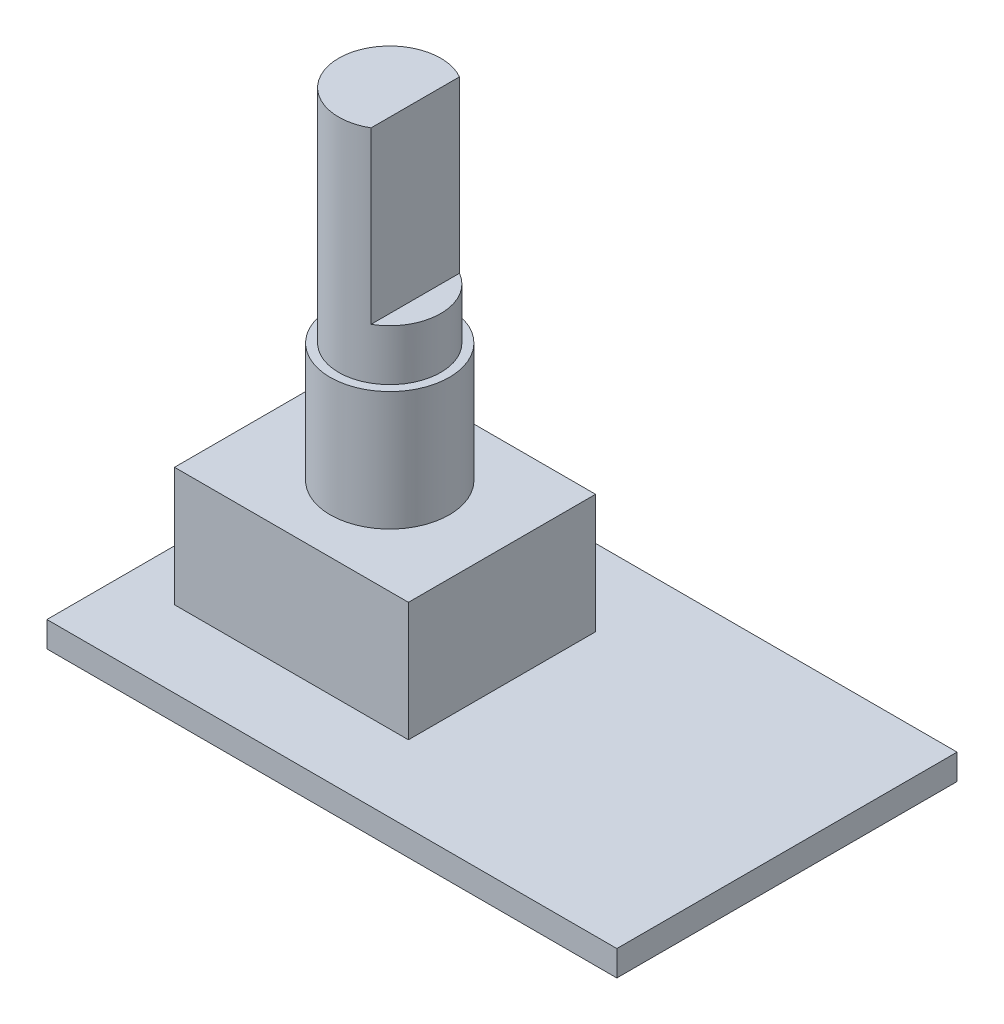
SolidWorks part; units mm, degrees
ref_plane "Front Plane" through (0, 0, 0) normal (0, 0, 1) x (1, 0, 0)
ref_plane "Top Plane" through (0, 0, 0) normal (0, 1, 0) x (1, 0, 0)
ref_plane "Right Plane" through (0, 0, 0) normal (1, 0, 0) x (0, 0, -1)
sketch "Sketch1" plane through (0, 0, 0) normal (0, 1, 0) x (1, 0, 0)
  line L1 (-8.8624, 8.0648) -> (24.6376, 8.0648)
  line L2 (-8.8624, 8.0648) -> (-8.8624, -11.9352)
  line L3 (-8.8624, -11.9352) -> (24.6376, -11.9352)
  line L4 (24.6376, 8.0648) -> (24.6376, -11.9352)
  dimension "D1" = 33.5
  dimension "D2" = 20
extrude "Boss-Extrude1" add sketch "Sketch1" along normal blind 1.5
sketch "Sketch2" plane through (0, 1.5, 0) normal (0, 1, 0) x (1, 0, 0)
  line L0 (24.6376, 8.0648) -> (-8.8624, 8.0648) construction
  line L1 (-5.8624, 3.5648) -> (7.8876, 3.5648)
  line L2 (-5.8624, 3.5648) -> (-5.8624, -7.4352)
  line L3 (-5.8624, -7.4352) -> (7.8876, -7.4352)
  line L4 (7.8876, 3.5648) -> (7.8876, -7.4352)
  line L5 (-8.8624, -11.9352) -> (24.6376, -11.9352) construction
  line L6 (-8.8624, 8.0648) -> (-8.8624, -11.9352) construction
  dimension "D1" = 4.5
  dimension "D2" = 4.5
  dimension "D3" = 3
  dimension "D4" = 13.75
extrude "Boss-Extrude2" add sketch "Sketch2" along normal blind 7
sketch "Sketch3" plane through (0, 8.5, 0) normal (0, 1, 0) x (1, 0, 0)
  line L0 (-5.8624, 3.5648) -> (-5.8624, -7.4352) construction
  circle A0 centre (1.1376, -1.7841) radius 3.5
  dimension "D1" = 7
  dimension "D2" = 7
extrude "Boss-Extrude3" add sketch "Sketch3" along normal blind 7
sketch "Sketch4" plane through (0, 15.5, 0) normal (0, 1, 0) x (1, 0, 0)
  circle A0 centre (1.1376, -1.7841) radius 3
extrude "Boss-Extrude4" add sketch "Sketch4" along normal blind 13
sketch "Sketch5" plane through (0, 28.5, 0) normal (0, 1, 0) x (1, 0, 0)
  line L1 (2.6376, -1.7841) -> (2.6376, 0.814)
  line L2 (2.6376, -1.7841) -> (2.6376, -4.3822)
  circle A0 centre (1.1376, -1.7841) radius 3 construction
  arc A1 (2.6376, -4.3822) -> (2.6376, 0.814) centre (1.1376, -1.7841) ccw
extrude "Cut-Extrude1" cut sketch "Sketch5" against normal blind 10
